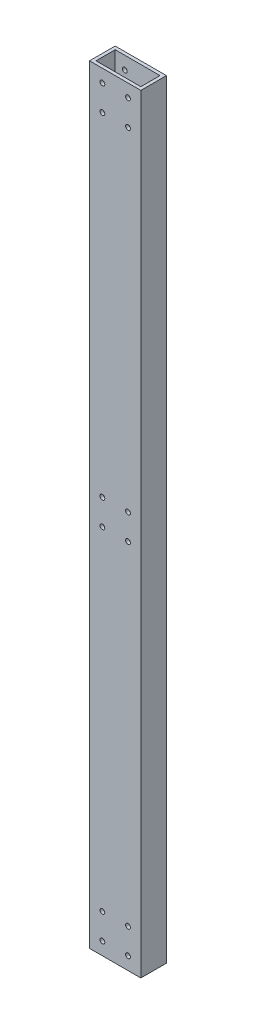
SolidWorks part; units mm, degrees
ref_plane "Front Plane" through (0, 0, 0) normal (0, 0, 1) x (1, 0, 0)
ref_plane "Top Plane" through (0, 0, 0) normal (0, 1, 0) x (1, 0, 0)
ref_plane "Right Plane" through (0, 0, 0) normal (1, 0, 0) x (0, 0, -1)
sketch "Sketch1" plane through (0, 0, 0) normal (0, 1, 0) x (1, 0, 0)
  line L1 (25.4, 12.7) -> (-25.4, 12.7)
  line L2 (25.4, 12.7) -> (25.4, -12.7)
  line L3 (25.4, -12.7) -> (-25.4, -12.7)
  line L4 (-25.4, 12.7) -> (-25.4, -12.7)
  line L5 (0, -12.7) -> (0, 12.7) construction
  line L6 (25.4, 0) -> (-25.4, 0) construction
  point P0 (0, 0)
  dimension "D1" = 50.8
  dimension "D2" = 25.4
extrude "Boss-Extrude1" add sketch "Sketch1" along normal mid plane 762
shell "Shell1" thickness 3.175
sketch "Sketch5" plane through (0, 0, 12.7) normal (0, 0, 1) x (1, 0, 0)
  line L0 (-25.4, 381) -> (25.4, 381) construction
  line L1 (12.7, 368.3) -> (-12.7, 368.3) construction
  line L2 (12.7, 368.3) -> (12.7, 342.9) construction
  line L3 (12.7, 342.9) -> (-12.7, 342.9) construction
  line L4 (-12.7, 368.3) -> (-12.7, 342.9) construction
  line L5 (0, 342.9) -> (0, 368.3) construction
  line L6 (12.7, 355.6) -> (-12.7, 355.6) construction
  line L7 (0, 0) -> (50000, 0) construction
  line L8 (12.7, -355.6) -> (-12.7, -355.6) construction
  line L9 (0, -342.9) -> (0, -368.3) construction
  line L10 (-12.7, -368.3) -> (-12.7, -342.9) construction
  line L11 (12.7, -342.9) -> (-12.7, -342.9) construction
  line L12 (12.7, -368.3) -> (12.7, -342.9) construction
  line L13 (12.7, -368.3) -> (-12.7, -368.3) construction
  circle A0 centre (-12.7, 368.3) radius 2.3813
  circle A1 centre (12.7, 368.3) radius 2.3813
  circle A2 centre (12.7, 342.9) radius 2.3813
  circle A3 centre (-12.7, 342.9) radius 2.3813
  circle A4 centre (-12.7, -342.9) radius 2.3813
  circle A5 centre (12.7, -342.9) radius 2.3813
  circle A6 centre (12.7, -368.3) radius 2.3813
  circle A7 centre (-12.7, -368.3) radius 2.3813
  circle A8 centre (-12.7, 12.7) radius 2.3813
  circle A9 centre (12.7, 12.7) radius 2.3813
  circle A10 centre (12.7, -12.7) radius 2.3813
  circle A11 centre (-12.7, -12.7) radius 2.3813
  point P8 (0, 355.6)
  point P27 (0, -355.6)
  point P32 (0, 0)
  point P33 (-12.7, 12.7)
  point P34 (12.7, 12.7)
  point P35 (0, 0)
  point P36 (0, 0)
  dimension "D1" = 4.7625
  dimension "D2" = 25.4
  dimension "D3" = 12.7
  dimension "D4" = 25.4
extrude "Cut-Extrude2" cut sketch "Sketch5" against normal through all both
